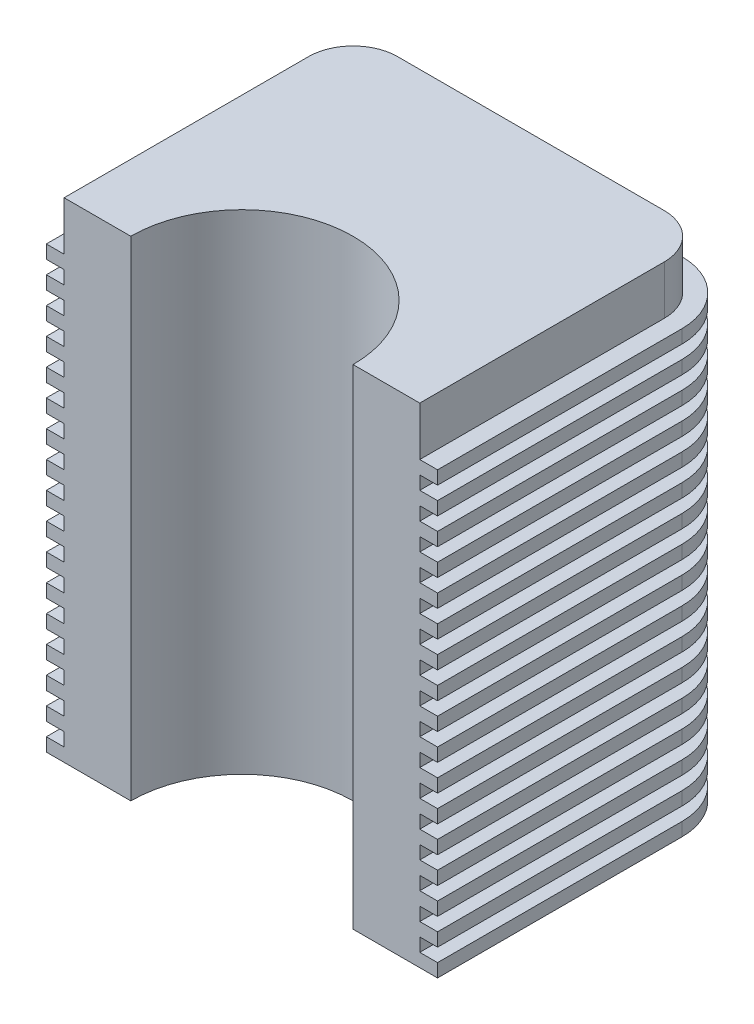
SolidWorks part; units mm, degrees
ref_plane "Front Plane" through (0, 0, 0) normal (0, 0, 1) x (1, 0, 0)
ref_plane "Top Plane" through (0, 0, 0) normal (0, 1, 0) x (1, 0, 0)
ref_plane "Right Plane" through (0, 0, 0) normal (1, 0, 0) x (0, 0, -1)
sketch "Sketch1" plane through (0, 0, 0) normal (0, 1, 0) x (1, 0, 0)
  line L0 (25, 0) -> (40, 0)
  line L1 (40, 0) -> (40, 55)
  line L2 (30, 65) -> (-30, 65)
  line L3 (0, 0) -> (0, 44.0704) construction
  line L4 (-40, 0) -> (-40, 55)
  line L5 (-25, 0) -> (-40, 0)
  line L6 (39, 0) -> (-39, 0) construction
  arc A0 (25, 0) -> (-25, 0) centre (0, 0) ccw
  arc A1 (40, 55) -> (30, 65) centre (30, 55) ccw
  arc A2 (-40, 55) -> (-30, 65) centre (-30, 55) cw
  point P1 (35, 0)
  point P9 (0, 65)
  point P13 (40, 65)
  point P16 (-40, 65)
  point P17 (-25, 0)
  point P20 (-25, 0)
  dimension "D1" = 50
  dimension "D4" = 10
  dimension "D2" = 15
  dimension "D3" = 65
extrude "Boss-Extrude2" add sketch "Sketch1" along normal blind 110
sketch "Sketch3" plane through (0, 0, 0) normal (0, -1, 0) x (1, 0, 0)
  line L1 (44, -55) -> (44, 0)
  line L2 (-30, -69) -> (30, -69)
  line L3 (-44, 0) -> (-44, -55)
  line L5 (-25, 0) -> (-40, 0)
  line L6 (-40, 0) -> (-40, -55)
  line L7 (-30, -65) -> (30, -65)
  line L8 (40, -55) -> (40, 0)
  line L9 (40, 0) -> (25, 0)
  line L10 (-25, 0) -> (-40, 0)
  line L11 (-40, 0) -> (-40, -55)
  line L12 (-30, -65) -> (30, -65)
  line L13 (40, -55) -> (40, 0)
  line L14 (40, 0) -> (25, 0)
  line L15 (-40, 0) -> (-44, 0)
  line L16 (40, 0) -> (44, 0)
  line L17 (-44, 4) -> (-44, -55) construction
  line L18 (-20.6155, 4) -> (-44, 4) construction
  line L19 (44, 4) -> (20.6155, 4) construction
  line L20 (44, -55) -> (44, 4) construction
  arc A1 (30, -69) -> (44, -55) centre (30, -55) ccw
  arc A2 (-44, -55) -> (-30, -69) centre (-30, -55) ccw
  arc A3 (-25, 0) -> (25, 0) centre (0, 0) ccw
  arc A4 (-40, -55) -> (-30, -65) centre (-30, -55) ccw
  arc A5 (30, -65) -> (40, -55) centre (30, -55) ccw
  arc A6 (-25, 0) -> (25, 0) centre (0, 0) ccw
  arc A7 (-40, -55) -> (-30, -65) centre (-30, -55) ccw
  arc A8 (30, -65) -> (40, -55) centre (30, -55) ccw
  arc A9 (-20.6155, 4) -> (20.6155, 4) centre (0, 0) ccw construction
  line M11 (-40, 0) -> (-40, -55)
  arc M12 (-40, -55) -> (-30, -65) centre (-30, -55) ccw
  line M13 (-30, -65) -> (30, -65)
  arc M14 (30, -65) -> (40, -55) centre (30, -55) ccw
  line M15 (40, -55) -> (40, 0)
  dimension "D1" = 0
  dimension "D2" = 4
extrude "Boss-Extrude4" add sketch "Sketch3" against normal blind 3 contours L3 A2 L2 A1 L1 L16 L15 M15 M14 M13 M12 M11
pattern_linear "LPattern1" count 17 spacing 6 along (0, 1, 0) of "Boss-Extrude4"
